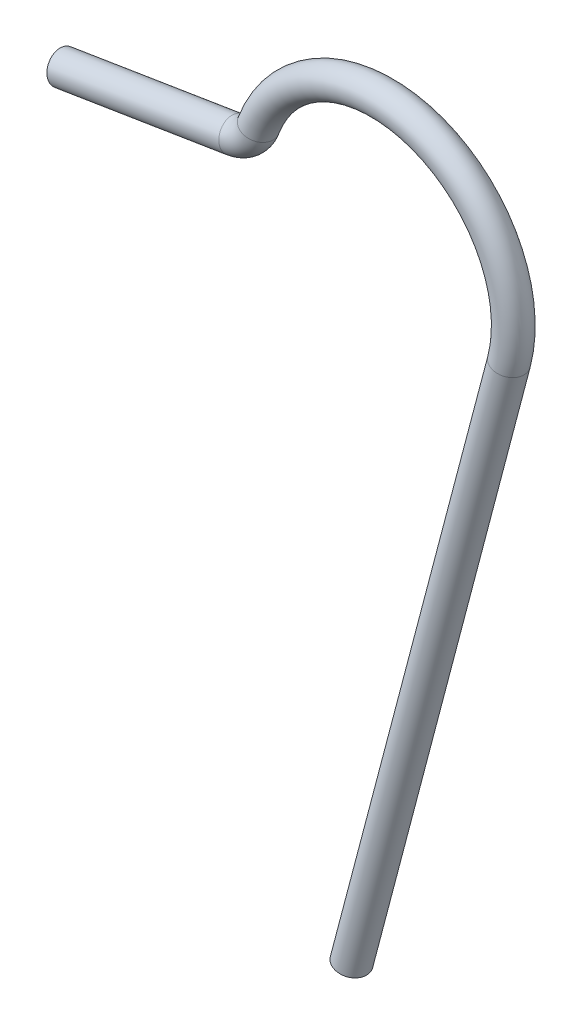
SolidWorks part; units mm, degrees
ref_plane "Alzado" through (0, 0, 0) normal (0, 0, 1) x (1, 0, 0)
ref_plane "Planta" through (0, 0, 0) normal (0, 1, 0) x (1, 0, 0)
ref_plane "Vista lateral" through (0, 0, 0) normal (1, 0, 0) x (0, 0, -1)
sketch "Croquis1" plane through (0, 0, 0) normal (0, 0, 1) x (1, 0, 0)
  line L0 (-3.6011, -0.2183) -> (-2.4903, -0.0391)
  line L3 (-3.274, -0.0642) -> (-3.0272, -0.0244) construction
  line L4 (-0.7166, -0.4255) -> (-1.7342, -4.2939)
  line L5 (-0.626, -0.4744) -> (-0.6666, -0.6284) construction
  arc A0 (-0.7166, -0.4255) -> (-2.3348, 0.0884) centre (-1.5386, -0.2093) ccw
  circle A1 centre (-1.5386, -0.2093) radius 0.75 construction
  arc A2 (-2.4903, -0.0391) -> (-2.3348, 0.0884) centre (-2.5221, 0.1584) ccw
  spline S0 degree 3 poles (-1.0423, -2.5153) (-2.2501, -4.1921) (0.6432, -5.5582) (-2.4292, -6.2518) knots 0 0 0 0 1 1 1 1 construction
  point P12 (-2.3671, -0.0192)
  dimension "D2" = 1.7
  dimension "D3" = 1.25
  dimension "D4" = 0.2
  dimension "D1" = 0.1
  dimension "D5" = 0.1
  dimension "D6" = 4
ref_plane "Plano1" through (-3.6011, -0.2183, 0) normal (0.9872, 0.1593, 0) x (0, 0, -1)
sketch "Croquis2" plane through (-3.6011, -0.2183, 0) normal (0.9872, 0.1593, 0) x (0, 0, -1)
  circle A0 centre (0, 0) radius 0.1
  dimension "D1" = 0.2
sweep "Barrer1" add profiles "Croquis2" path "Croquis1"
